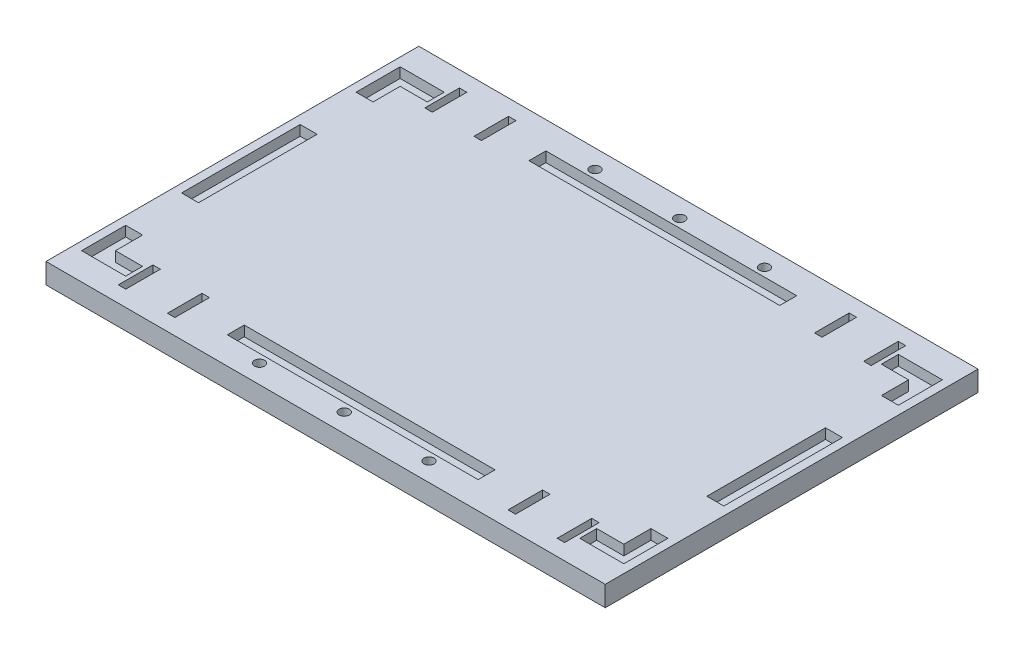
SolidWorks part; units mm, degrees
ref_plane "Front Plane" through (0, 0, 0) normal (0, 0, 1) x (1, 0, 0)
ref_plane "Top Plane" through (0, 0, 0) normal (0, 1, 0) x (1, 0, 0)
ref_plane "Right Plane" through (0, 0, 0) normal (1, 0, 0) x (0, 0, -1)
sketch "Sketch1" plane through (0, 0, 0) normal (0, 1, 0) x (1, 0, 0)
  line L1 (-95.1587, 56.746) -> (69.8413, 56.746)
  line L2 (-95.1587, 56.746) -> (-95.1587, -53.254)
  line L3 (-95.1587, -53.254) -> (69.8413, -53.254)
  line L4 (69.8413, 56.746) -> (69.8413, -53.254)
  dimension "D1" = 110
  dimension "D2" = 165
extrude "Boss-Extrude1" add sketch "Sketch1" along normal blind 6 contours L1 L4 L3 L2
sketch "Sketch2" plane through (0, 6, 0) normal (0, 1, 0) x (1, 0, 0)
  line L0 (-70.1587, 54.246) -> (-37.6587, 54.246) construction
  line L12 (-95.1587, 56.746) -> (69.8413, 56.746) construction
  line L13 (-92.6587, 48.746) -> (67.3413, 48.746) construction
  line L32 (-92.6587, 48.746) -> (-92.6587, -45.254) construction
  line L33 (-92.6587, -45.254) -> (67.3413, -45.254) construction
  line L34 (67.3413, 48.746) -> (67.3413, -45.254) construction
  line L36 (-95.1587, -53.254) -> (69.8413, -53.254) construction
  line L37 (-95.1587, 56.746) -> (-95.1587, -53.254) construction
  line L38 (69.8413, 56.746) -> (69.8413, -53.254) construction
  line L39 (-92.6587, 48.746) -> (-92.6587, 35.746)
  line L40 (-92.6587, 35.746) -> (-87.6587, 35.746)
  line L41 (-87.6587, 35.746) -> (-87.6587, 43.746)
  line L42 (-87.6587, 43.746) -> (-79.6587, 43.746)
  line L43 (-79.6587, 43.746) -> (-79.6587, 48.746)
  line L44 (-79.6587, 48.746) -> (-92.6587, 48.746)
  line L45 (-106.2643, 1.746) -> (82.4028, 1.746) construction
  line L46 (-12.6587, 67.4112) -> (-12.6587, -62.8099) construction
  line L47 (-79.6587, -40.254) -> (-79.6587, -45.254)
  line L48 (-87.6587, -40.254) -> (-79.6587, -40.254)
  line L49 (-87.6587, -32.254) -> (-87.6587, -40.254)
  line L50 (-92.6587, -32.254) -> (-87.6587, -32.254)
  line L51 (-92.6587, -45.254) -> (-92.6587, -32.254)
  line L52 (-79.6587, -45.254) -> (-92.6587, -45.254)
  line L53 (54.3413, 43.746) -> (54.3413, 48.746)
  line L54 (62.3413, 43.746) -> (54.3413, 43.746)
  line L55 (62.3413, 35.746) -> (62.3413, 43.746)
  line L56 (67.3413, 35.746) -> (62.3413, 35.746)
  line L57 (67.3413, 48.746) -> (67.3413, 35.746)
  line L58 (54.3413, 48.746) -> (67.3413, 48.746)
  line L59 (62.3413, -40.254) -> (54.3413, -40.254)
  line L60 (62.3413, -32.254) -> (62.3413, -40.254)
  line L61 (67.3413, -32.254) -> (62.3413, -32.254)
  line L62 (67.3413, -45.254) -> (67.3413, -32.254)
  line L63 (54.3413, -45.254) -> (67.3413, -45.254)
  line L64 (54.3413, -40.254) -> (54.3413, -45.254)
  line L65 (67.3413, -15.754) -> (62.3413, -15.754)
  line L66 (-92.6587, 19.246) -> (-87.6587, 19.246)
  line L67 (-92.6587, 19.246) -> (-92.6587, -15.754)
  line L68 (-92.6587, -15.754) -> (-87.6587, -15.754)
  line L69 (-87.6587, 19.246) -> (-87.6587, -15.754)
  line L70 (62.3413, 19.246) -> (62.3413, -15.754)
  line L71 (67.3413, 19.246) -> (62.3413, 19.246)
  line L72 (67.3413, 19.246) -> (67.3413, -15.754)
  line L73 (-49.6587, -40.254) -> (24.3413, -40.254)
  line L74 (-49.6587, 48.746) -> (24.3413, 48.746)
  line L75 (-49.6587, 48.746) -> (-49.6587, 43.746)
  line L76 (-49.6587, 43.746) -> (24.3413, 43.746)
  line L77 (24.3413, 48.746) -> (24.3413, 43.746)
  line L78 (24.3413, -45.254) -> (24.3413, -40.254)
  line L79 (-49.6587, -45.254) -> (24.3413, -45.254)
  line L80 (-49.6587, -45.254) -> (-49.6587, -40.254)
  line L81 (-95.1587, 52.0662) -> (-70.1587, 52.0662) construction
  line L82 (-70.1587, 52.0662) -> (-70.1587, 45.4053) construction
  line L83 (-78.5087, 52.0662) -> (-76.3087, 52.0662)
  line L84 (-78.5087, 52.0662) -> (-78.5087, 41.8662)
  line L85 (-78.5087, 41.8662) -> (-76.3087, 41.8662)
  line L86 (-76.3087, 52.0662) -> (-76.3087, 41.8662)
  line L87 (-61.8087, 41.8662) -> (-64.0087, 41.8662)
  line L88 (-64.0087, 52.0662) -> (-64.0087, 41.8662)
  line L89 (-61.8087, 52.0662) -> (-64.0087, 52.0662)
  line L90 (-61.8087, 52.0662) -> (-61.8087, 41.8662)
  line L91 (53.1913, 41.8662) -> (50.9913, 41.8662)
  line L92 (50.9913, 52.0662) -> (50.9913, 41.8662)
  line L93 (53.1913, 52.0662) -> (50.9913, 52.0662)
  line L94 (53.1913, 52.0662) -> (53.1913, 41.8662)
  line L95 (36.4913, 52.0662) -> (36.4913, 41.8662)
  line L96 (36.4913, 52.0662) -> (38.6913, 52.0662)
  line L97 (38.6913, 52.0662) -> (38.6913, 41.8662)
  line L98 (36.4913, 41.8662) -> (38.6913, 41.8662)
  line L99 (53.1913, -48.5742) -> (53.1913, -38.3742)
  line L100 (53.1913, -48.5742) -> (50.9913, -48.5742)
  line L101 (50.9913, -48.5742) -> (50.9913, -38.3742)
  line L102 (53.1913, -38.3742) -> (50.9913, -38.3742)
  line L103 (36.4913, -48.5742) -> (38.6913, -48.5742)
  line L104 (38.6913, -48.5742) -> (38.6913, -38.3742)
  line L105 (36.4913, -38.3742) -> (38.6913, -38.3742)
  line L106 (36.4913, -48.5742) -> (36.4913, -38.3742)
  line L107 (-61.8087, -48.5742) -> (-61.8087, -38.3742)
  line L108 (-61.8087, -48.5742) -> (-64.0087, -48.5742)
  line L109 (-64.0087, -48.5742) -> (-64.0087, -38.3742)
  line L110 (-61.8087, -38.3742) -> (-64.0087, -38.3742)
  line L111 (-78.5087, -38.3742) -> (-76.3087, -38.3742)
  line L112 (-76.3087, -48.5742) -> (-76.3087, -38.3742)
  line L113 (-78.5087, -48.5742) -> (-76.3087, -48.5742)
  line L114 (-78.5087, -48.5742) -> (-78.5087, -38.3742)
  dimension "D1" = 8
  dimension "D2" = 8
  dimension "D3" = 2.5
  dimension "D4" = 2.5
  dimension "D5" = 5
  dimension "D6" = 5
  dimension "D7" = 8
  dimension "D8" = 8
  dimension "D9" = 35
  dimension "D10" = 16.5
  dimension "D11" = 30
  dimension "D12" = 30
  dimension "D13" = 25
  dimension "D14" = 6.15
  dimension "D15" = 2.2
  dimension "D16" = 10.2
  dimension "D17" = 32.5
  dimension "D19" = 2.5
extrude "Cut-Extrude1" cut sketch "Sketch2" against normal blind 3
sketch "Sketch3" plane through (0, 6, 0) normal (0, 1, 0) x (1, 0, 0)
  line L1 (-43.9266, 51.246) -> (20.1772, 51.246) construction
  line L2 (-12.6587, 60.641) -> (-12.6587, -65.6147) construction
  line L3 (12.3413, 60.641) -> (12.3413, 49.6141) construction
  line L4 (-37.6587, 59.814) -> (-37.6587, 50.7541) construction
  line L5 (-109.7338, 1.746) -> (100.3995, 1.746) construction
  line L6 (-95.1587, 56.746) -> (69.8413, 56.746) construction
  circle A0 centre (-37.6587, 51.246) radius 1.5
  circle A1 centre (12.3413, 51.246) radius 1.5
  circle A3 centre (-12.6587, 51.246) radius 1.5
  circle A4 centre (12.3413, -47.754) radius 1.5
  circle A5 centre (-12.6587, -47.754) radius 1.5
  circle A6 centre (-37.6587, -47.754) radius 1.5
  dimension "D2" = 3
  dimension "D3" = 3
  dimension "D1" = 5.5
extrude "Cut-Extrude2" cut sketch "Sketch3" against normal through all
